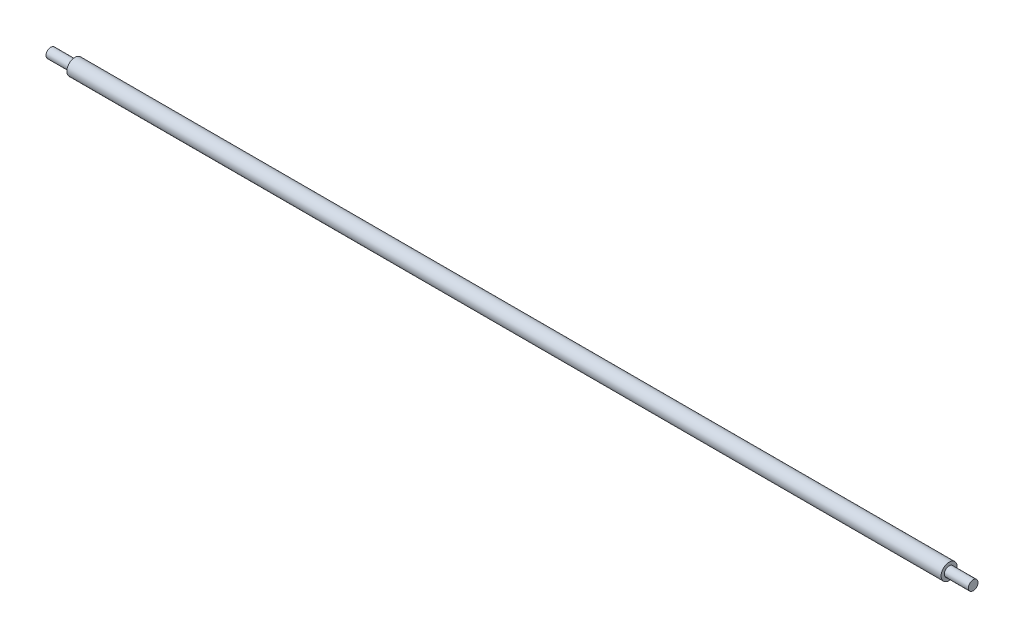
SolidWorks part; units mm, degrees
ref_plane "Спереди" through (0, 0, 0) normal (0, 0, 1) x (1, 0, 0)
ref_plane "Сверху" through (0, 0, 0) normal (0, 1, 0) x (1, 0, 0)
ref_plane "Справа" through (0, 0, 0) normal (1, 0, 0) x (0, 0, -1)
sketch "Эскиз1" plane through (0, 0, 0) normal (1, 0, 0) x (0, 0, -1)
  circle A0 centre (0, 0) radius 5
  dimension "D1" = 10
extrude "Бобышка-Вытянуть1" add sketch "Эскиз1" along normal blind 275 and the other way blind 270
sketch "Эскиз2" plane through (-270, 0, 0) normal (-1, 0, 0) x (0, 0, 1)
  circle A0 centre (0, 0) radius 3
  dimension "D1" = 6
extrude "Бобышка-Вытянуть2" add sketch "Эскиз2" along normal blind 15
cosmetic thread "Условное изображение резьбы4"
sketch "Эскиз7" plane through (275, 0, 0) normal (1, 0, 0) x (0, 0, -1)
  circle A0 centre (0, 0) radius 3
  dimension "D1" = 6
extrude "Бобышка-Вытянуть3" add sketch "Эскиз7" along normal blind 15
cosmetic thread "Условное изображение резьбы5" parameters "D1"=14.9999, "D2"=4.891
